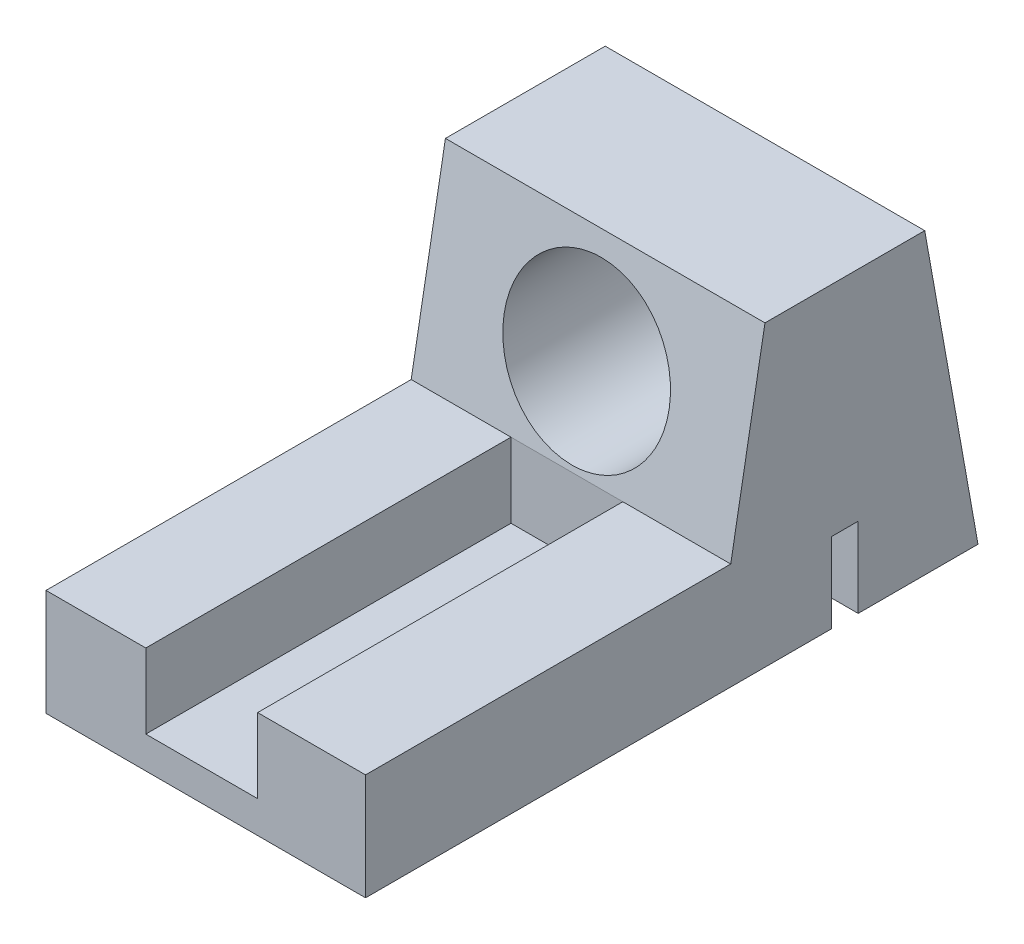
SolidWorks part; units mm, degrees
ref_plane "정면" through (0, 0, 0) normal (0, 0, 1) x (1, 0, 0)
ref_plane "윗면" through (0, 0, 0) normal (0, 1, 0) x (1, 0, 0)
ref_plane "우측면" through (0, 0, 0) normal (1, 0, 0) x (0, 0, -1)
sketch "스케치3" plane through (0, 0, 0) normal (1, 0, 0) x (0, 0, -1)
  line L0 (0, 4.5456) -> (0, -51.4544) construction
  line L1 (-25, -51.4544) -> (25, -51.4544)
  line L2 (-15, 4.5456) -> (15, 4.5456)
  line L3 (-15, 4.5456) -> (-25, -51.4544)
  line L4 (15, 4.5456) -> (25, -51.4544)
  dimension "D2" = 50
  dimension "D3" = 30
  dimension "D4" = 56
extrude "보스-돌출1" add sketch "스케치3" along normal blind 60
sketch "스케치4" plane through (0, 0, 0) normal (0, 0, 1) x (1, 0, 0)
  line L0 (-1.9678, -14.9544) -> (61.9678, -14.9544) construction
  line L1 (30, -51.4544) -> (30, 7.4262) construction
  line L2 (60, -51.4544) -> (0, -51.4544) construction
  circle A0 centre (30, -14.9544) radius 15.5
  dimension "D1" = 31
  dimension "D2" = 21
extrude "컷-돌출1" cut sketch "스케치4" along normal blind 40 and the other way blind 29
sketch "스케치5" plane through (0, 0, 0) normal (1, 0, 0) x (0, 0, -1)
  line L0 (0, 7.2507) -> (0, -19.0866) construction
  line L1 (-25, -51.4544) -> (25, -51.4544) construction
  line L2 (2.5, -66.4544) -> (-2.5, -66.4544)
  line L3 (2.5, -66.4544) -> (2.5, -36.4544)
  line L4 (2.5, -36.4544) -> (-2.5, -36.4544)
  line L5 (-2.5, -66.4544) -> (-2.5, -36.4544)
  line L6 (2.5, -66.4544) -> (-2.5, -36.4544) construction
  line L7 (2.5, -36.4544) -> (-2.5, -66.4544) construction
  point P3 (0, -51.4544)
  dimension "D1" = 5
  dimension "D2" = 30
extrude "컷-돌출2" cut sketch "스케치5" along normal through all
ref_plane "평면1" through (0, -51.4544, 0) normal (0, -1, 0) x (-1, 0, 0)
sketch "스케치7" plane through (0, -51.4544, 0) normal (0, -1, 0) x (-1, 0, 0)
  line L0 (-60, -25) -> (-60, -2.5) construction
  line L1 (-60, -4.5751) -> (0, -4.5751)
  line L2 (-60, -4.5751) -> (-60, -90)
  line L3 (-60, -90) -> (0, -90)
  line L4 (0, -4.5751) -> (0, -90)
  line L5 (-60, -25) -> (0, -25) construction
  dimension "D1" = 65
extrude "보스-돌출2" add sketch "스케치7" against normal blind 20
sketch "스케치8" plane through (0, 0, 0) normal (0, 1, 0) x (1, 0, 0)
  line L1 (29.2384, 16.9272) -> (29.2384, -68.3552) construction
  line L4 (60, -21.4286) -> (0, -21.4286) construction
  line L6 (18.7384, -21.4286) -> (39.7384, -21.4286)
  line L7 (18.7384, -21.4286) -> (18.7384, -90)
  line L8 (18.7384, -90) -> (39.7384, -90)
  line L9 (39.7384, -21.4286) -> (39.7384, -90)
  line L10 (60, -90) -> (0, -90) construction
  dimension "D2" = 10.5
  dimension "D3" = 10.5
extrude "컷-돌출3" cut sketch "스케치8" against normal blind 14 from surface at -31.4544 starting at face at (30, -31.4544, 55.7143)
